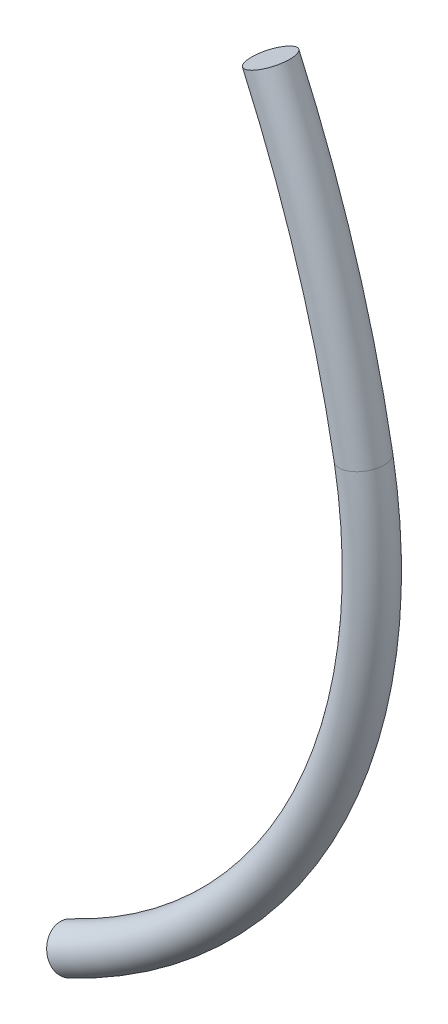
SolidWorks part; units mm, degrees
ref_plane "Front" through (0, 0, 0) normal (0, 0, 1) x (1, 0, 0)
ref_plane "Top" through (0, 0, 0) normal (0, 1, 0) x (1, 0, 0)
ref_plane "Right" through (0, 0, 0) normal (1, 0, 0) x (0, 0, -1)
sketch "Sketch1" plane through (0, 0, 0) normal (0, 0, 1) x (1, 0, 0)
  arc A0 (3623.9082, -3191.1987) -> (4336.743, -1804.0024) centre (3074.3815, -2032.0655) ccw
  arc A1 (1640.1048, -2343.3491) -> (3623.9082, -3191.1987) centre (3006.9834, -1889.9007) ccw construction
  arc A2 (4336.743, -1804.0024) -> (4111.7464, -1077.9471) centre (1257.7011, -2360.274) ccw
  dimension "D1" = 1676.4
  dimension "D2" = 762
sketch "Sketch3" plane through (1723.6182, 817.1401, 0) normal (0.9036, 0.4284, 0) x (0, 0, -1)
  circle A0 centre (0, -4435.9759) radius 50.8
sweep "Sweep1" add profiles "Sketch3" path "Sketch1"
